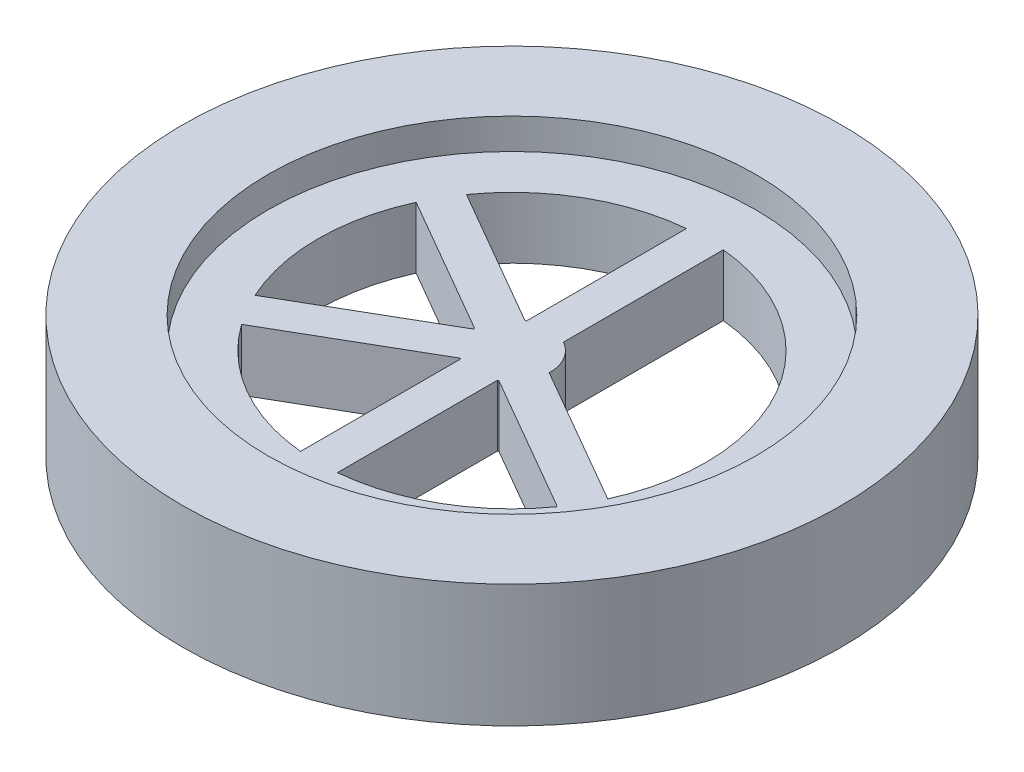
SolidWorks part; units mm, degrees
ref_plane "Front Plane" through (0, 0, 0) normal (0, 0, 1) x (1, 0, 0)
ref_plane "Top Plane" through (0, 0, 0) normal (0, 1, 0) x (1, 0, 0)
ref_plane "Right Plane" through (0, 0, 0) normal (1, 0, 0) x (0, 0, -1)
sketch "Sketch1" plane through (0, 0, 0) normal (0, 1, 0) x (1, 0, 0)
  circle A0 centre (0, 0) radius 53.6953
extrude "Boss-Extrude2" add sketch "Sketch1" along normal mid plane 20 contours A0
sketch "Sketch3" plane through (0, 0, 0) normal (0, 1, 0) x (1, 0, 0)
  circle A0 centre (0, 0) radius 39.7331
extrude "Cut-Extrude2" cut sketch "Sketch3" against normal mid plane 20
sketch "Sketch4" plane through (0, 0, 0) normal (0, 1, 0) x (1, 0, 0)
  circle A1 centre (0, 0) radius 31.5846
  circle A2 centre (0, 0) radius 39.7331
extrude "Boss-Extrude3" add sketch "Sketch4" along normal mid plane 10 contours A2 A1
sketch "Sketch6" plane through (0, 0, 0) normal (0, 1, 0) x (1, 0, 0)
  line L0 (0, 0) -> (0, 53.6953) construction
  line L1 (3, 5.3871) -> (3, 39.6197)
  line L2 (-3, 5.3871) -> (-3, 39.6197)
  line L3 (-3, 39.6197) -> (3, 39.6197)
  line L5 (-3, 0) -> (-3, 53.6953) construction
  line L6 (3, 0) -> (3, 53.6953) construction
  arc A0 (-3, 5.3871) -> (3, 5.3871) centre (0, 0) ccw
  circle A1 centre (0, 0) radius 53.6953 construction
  circle A4 centre (0, 0) radius 39.7331 construction
  dimension "D1" = 3
  dimension "D2" = 3
extrude "Boss-Extrude4" add sketch "Sketch6" along normal mid plane 10
pattern_circular "CirPattern3" count 5 over 240 about axis through (0, 0, 0) along (0, 1, 0) of "Boss-Extrude4"
